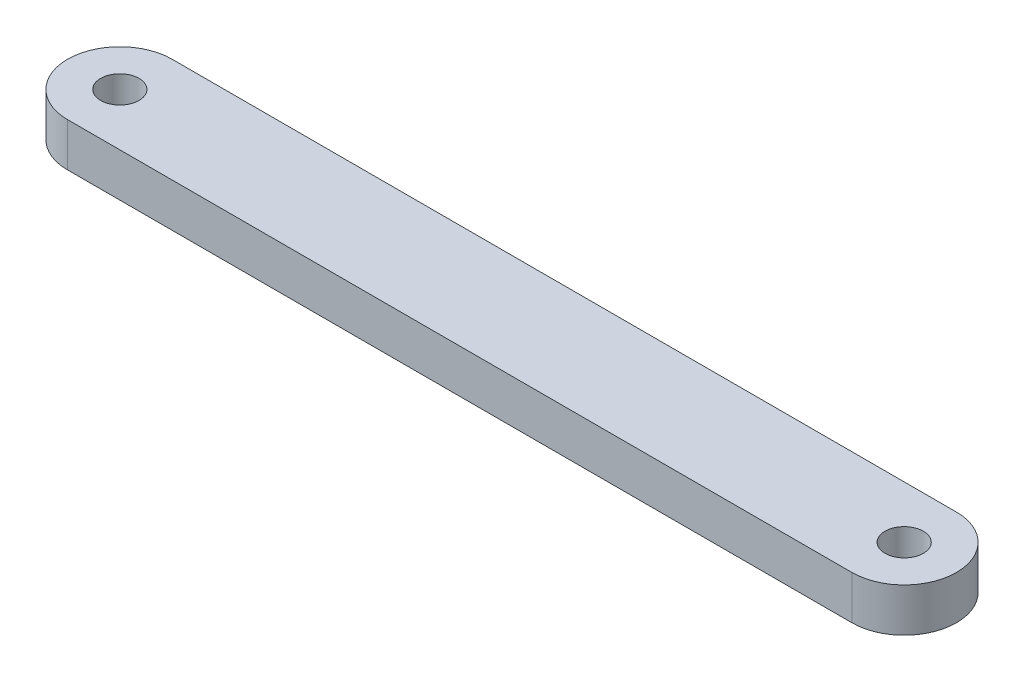
SolidWorks part; units mm, degrees
material "ABS"
ref_plane "Front Plane" through (0, 0, 0) normal (0, 0, 1) x (1, 0, 0)
ref_plane "Top Plane" through (0, 0, 0) normal (0, 1, 0) x (1, 0, 0)
ref_plane "Right Plane" through (0, 0, 0) normal (1, 0, 0) x (0, 0, -1)
sketch "Sketch3" plane through (0, 0, 0) normal (0, 1, 0) x (-1, 0, 0)
  line L0 (-22.5, 0) -> (22.5, 0) construction
  line L6 (22.5, -3) -> (-22.5, -3)
  line L7 (-22.5, 3) -> (22.5, 3)
  circle A0 centre (-22.5, 0) radius 3
  circle A1 centre (-22.5, 0) radius 1.1
  circle A2 centre (22.5, 0) radius 1.1
  circle A3 centre (22.5, 0) radius 3
  point P6 (0, 0)
  point P11 (0, 0)
  point P12 (0, 0)
  point P13 (0, 0)
  point P14 (0, 0)
  point P15 (0, 0)
  point P17 (22.5, 1.767)
  point P18 (22.5, 3)
  dimension "D1" = 45
  dimension "D2" = 2.2
  dimension "D3" = 6
  dimension "D4" = 2.2
  dimension "D5" = 6
extrude "Boss-Extrude1" add sketch "Sketch3" along normal blind 2.5
